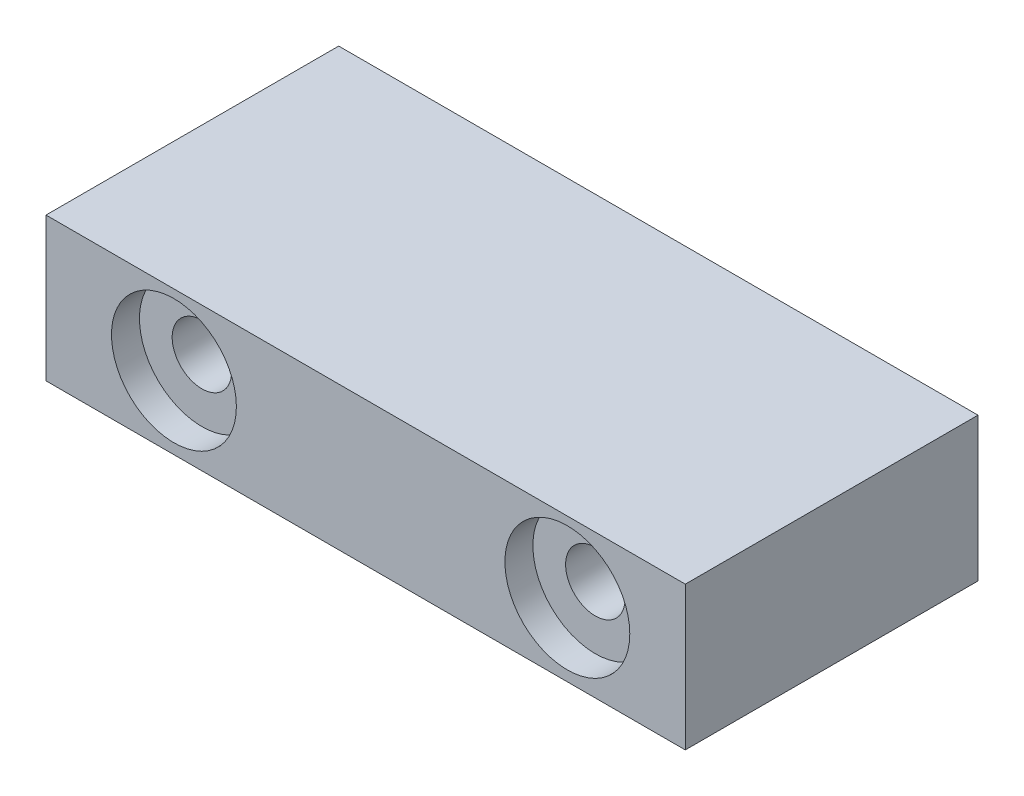
SolidWorks part; units mm, degrees
ref_plane "Front Plane" through (0, 0, 0) normal (0, 0, 1) x (1, 0, 0)
ref_plane "Top Plane" through (0, 0, 0) normal (0, 1, 0) x (1, 0, 0)
ref_plane "Right Plane" through (0, 0, 0) normal (1, 0, 0) x (0, 0, -1)
sketch "Sketch1" plane through (0, 0, 0) normal (0, 0, 1) x (1, 0, 0)
  line L0 (-8.125, 3.65) -> (-8.125, 0)
  line L1 (-8.125, 0) -> (8.125, 0)
  line L2 (-8.125, 3.65) -> (8.125, 3.65)
  line L3 (8.125, 3.65) -> (8.125, 0)
  dimension "D1" = 3.65
  dimension "D2" = 16.25
extrude "Boss-Extrude1" add sketch "Sketch1" along normal blind 7.44
sketch "Sketch8" plane through (0, 0, 7.44) normal (0, 0, 1) x (1, 0, 0)
  line L2 (8.125, 3.65) -> (-8.125, 3.65) construction
  point P0 (-4.8733, 1.85)
  point P2 (5.1267, 1.85)
  point P5 (-5.3745, 1.8621)
  point P6 (5.1146, 2.0478)
  point P12 (-4.8733, 2.0478)
  dimension "D1" = 10
  dimension "D2" = 1.8
hole_wizard "CBORE for #00 Binding Head Machine Screw1" positions "Sketch8" profile "Sketch9" counterbore size "#00" standard "ANSI Inch"
sketch "Sketch9" plane through (-4.8733, 1.85, 7.44) normal (1, 0, 0) x (0, -1, 0)
  line L0 (0, 0) -> (0, 5.454)
  line L1 (0, 5.454) -> (0.7556, 5)
  line L2 (0.7556, 5) -> (0.7556, 0.7112)
  line L3 (0.7556, 0.7112) -> (1.5875, 0.7112)
  line L4 (1.5875, 0.7112) -> (1.5875, 0)
  line L5 (1.5875, 0) -> (0, 0)
  line L10 (0, 5.454) -> (-0.7557, 5) construction
  line L11 (0, -6.35) -> (0, 107.95) construction
  dimension "Hole Dia." = 1.5113
  dimension "Hole Depth" = 5
  dimension "C'Bore Dia." = 3.175
  dimension "C'Bore Depth" = 0.7112
  dimension "Drill Angle" = 118
